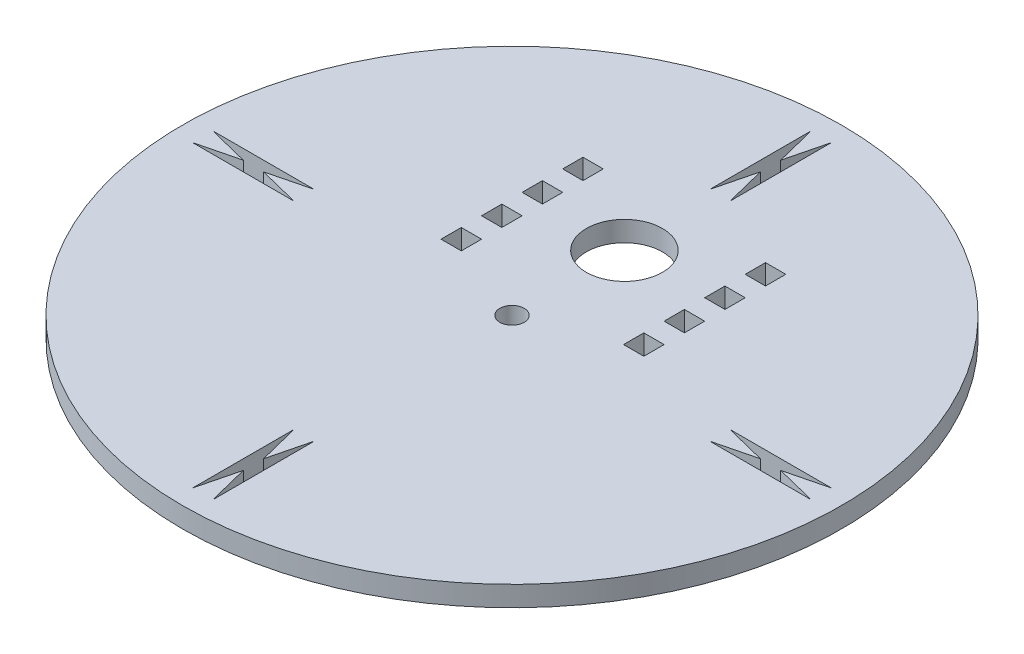
SolidWorks part; units mm, degrees
ref_plane "Front Plane" through (0, 0, 0) normal (0, 0, 1) x (1, 0, 0)
ref_plane "Top Plane" through (0, 0, 0) normal (0, 1, 0) x (1, 0, 0)
ref_plane "Right Plane" through (0, 0, 0) normal (1, 0, 0) x (0, 0, -1)
sketch "Sketch1" plane through (0, 0, 0) normal (0, 1, 0) x (1, 0, 0)
  line L0 (-62.9674, 163.9506) -> (-62.9674, -1.1494) construction
  line L1 (-145.5174, 81.4006) -> (19.5826, 81.4006) construction
  line L2 (-37.5674, 188.935) -> (-37.5674, -106.0892) construction
  line L3 (-173.8413, 106.8006) -> (52.6322, 106.8006) construction
  line L4 (-150.5974, 132.2006) -> (24.6626, 132.2006) construction
  line L5 (-88.3674, 188.935) -> (-88.3674, -106.0892) construction
  line L6 (-83.2874, 114.4206) -> (-83.2874, 109.3406)
  line L7 (-88.3674, 89.0206) -> (-83.2874, 89.0206)
  line L8 (-88.3674, 89.0206) -> (-88.3674, 94.1006)
  line L9 (-88.3674, 94.1006) -> (-83.2874, 94.1006)
  line L10 (-83.2874, 89.0206) -> (-83.2874, 94.1006)
  line L11 (-88.3674, 99.1806) -> (-83.2874, 99.1806)
  line L12 (-88.3674, 99.1806) -> (-88.3674, 104.2606)
  line L13 (-88.3674, 104.2606) -> (-83.2874, 104.2606)
  line L14 (-83.2874, 99.1806) -> (-83.2874, 104.2606)
  line L15 (-88.3674, 109.3406) -> (-83.2874, 109.3406)
  line L16 (-88.3674, 114.4206) -> (-88.3674, 109.3406)
  line L17 (-88.3674, 114.4206) -> (-83.2874, 114.4206)
  line L18 (-83.2874, 124.5806) -> (-83.2874, 119.5006)
  line L19 (-88.3674, 119.5006) -> (-83.2874, 119.5006)
  line L20 (-88.3674, 124.5806) -> (-88.3674, 119.5006)
  line L21 (-88.3674, 124.5806) -> (-83.2874, 124.5806)
  line L22 (-37.5674, 124.5806) -> (-42.6474, 124.5806)
  line L23 (-37.5674, 124.5806) -> (-37.5674, 119.5006)
  line L24 (-37.5674, 119.5006) -> (-42.6474, 119.5006)
  line L25 (-42.6474, 124.5806) -> (-42.6474, 119.5006)
  line L26 (-37.5674, 114.4206) -> (-42.6474, 114.4206)
  line L27 (-37.5674, 114.4206) -> (-37.5674, 109.3406)
  line L28 (-37.5674, 109.3406) -> (-42.6474, 109.3406)
  line L29 (-42.6474, 99.1806) -> (-42.6474, 104.2606)
  line L30 (-37.5674, 104.2606) -> (-42.6474, 104.2606)
  line L31 (-37.5674, 99.1806) -> (-37.5674, 104.2606)
  line L32 (-37.5674, 99.1806) -> (-42.6474, 99.1806)
  line L33 (-42.6474, 89.0206) -> (-42.6474, 94.1006)
  line L34 (-37.5674, 94.1006) -> (-42.6474, 94.1006)
  line L35 (-37.5674, 89.0206) -> (-37.5674, 94.1006)
  line L36 (-37.5674, 89.0206) -> (-42.6474, 89.0206)
  line L37 (-42.6474, 114.4206) -> (-42.6474, 109.3406)
  circle A0 centre (-62.9674, 81.4006) radius 82.55
  circle A1 centre (-62.9674, 81.4006) radius 3.048
  circle A2 centre (-62.9674, 109.5565) radius 9.525
  dimension "D1" = 165.1
  dimension "D12" = 6.096
  dimension "D13" = 28.1559
  dimension "D14" = 19.05
  dimension "D2" = 25.4
  dimension "D3" = 25.4
  dimension "D4" = 25.4
  dimension "D5" = 25.4
  dimension "D6" = 5.08
  dimension "D7" = 5.08
  dimension "D8" = 5.08
  dimension "D9" = 5.08
  dimension "D10" = 5.08
  dimension "D11" = 2.54
extrude "Boss-Extrude1" add sketch "Sketch1" along normal blind 5.08
sketch "Sketch2" plane through (0, 5.08, 0) normal (0, 1, 0) x (1, 0, 0)
  line L0 (-62.9674, -1.1494) -> (-62.9674, 163.9506) construction
  line L1 (-145.5174, 81.4006) -> (19.5826, 81.4006) construction
  line L2 (-62.9674, 148.7106) -> (-60.4274, 158.8706)
  line L3 (-60.4274, 158.8706) -> (-60.4274, 133.4706)
  line L4 (-60.4274, 133.4706) -> (-62.9674, 143.6306)
  line L5 (-65.5074, 133.4706) -> (-62.9674, 143.6306)
  line L6 (-65.5074, 158.8706) -> (-65.5074, 133.4706)
  line L7 (-62.9674, 148.7106) -> (-65.5074, 158.8706)
  line L8 (4.3426, 81.4006) -> (14.5026, 78.8606)
  line L9 (14.5026, 78.8606) -> (-10.8974, 78.8606)
  line L10 (-10.8974, 78.8606) -> (-0.7374, 81.4006)
  line L11 (-10.8974, 83.9406) -> (-0.7374, 81.4006)
  line L12 (14.5026, 83.9406) -> (-10.8974, 83.9406)
  line L13 (4.3426, 81.4006) -> (14.5026, 83.9406)
  line L14 (-62.9674, 14.0906) -> (-65.5074, 3.9306)
  line L15 (-65.5074, 3.9306) -> (-65.5074, 29.3306)
  line L16 (-65.5074, 29.3306) -> (-62.9674, 19.1706)
  line L17 (-60.4274, 29.3306) -> (-62.9674, 19.1706)
  line L18 (-60.4274, 3.9306) -> (-60.4274, 29.3306)
  line L19 (-62.9674, 14.0906) -> (-60.4274, 3.9306)
  line L20 (-130.2774, 81.4006) -> (-140.4374, 83.9406)
  line L21 (-140.4374, 83.9406) -> (-115.0374, 83.9406)
  line L22 (-115.0374, 83.9406) -> (-125.1974, 81.4006)
  line L23 (-115.0374, 78.8606) -> (-125.1974, 81.4006)
  line L24 (-140.4374, 78.8606) -> (-115.0374, 78.8606)
  line L25 (-130.2774, 81.4006) -> (-140.4374, 78.8606)
  circle A0 centre (-62.9674, 81.4006) radius 82.55 construction
  point P13 (-62.9674, 81.4006)
  point P35 (-60.4274, 78.8606)
  point P36 (-62.9674, 81.4006)
  dimension "D1" = 2.54
  dimension "D2" = 10.16
  dimension "D3" = 10.16
  dimension "D4" = 25.4
  dimension "D5" = 5.08
  dimension "D6" = 4
extrude "Cut-Extrude1" cut sketch "Sketch2" against normal blind 5.08
